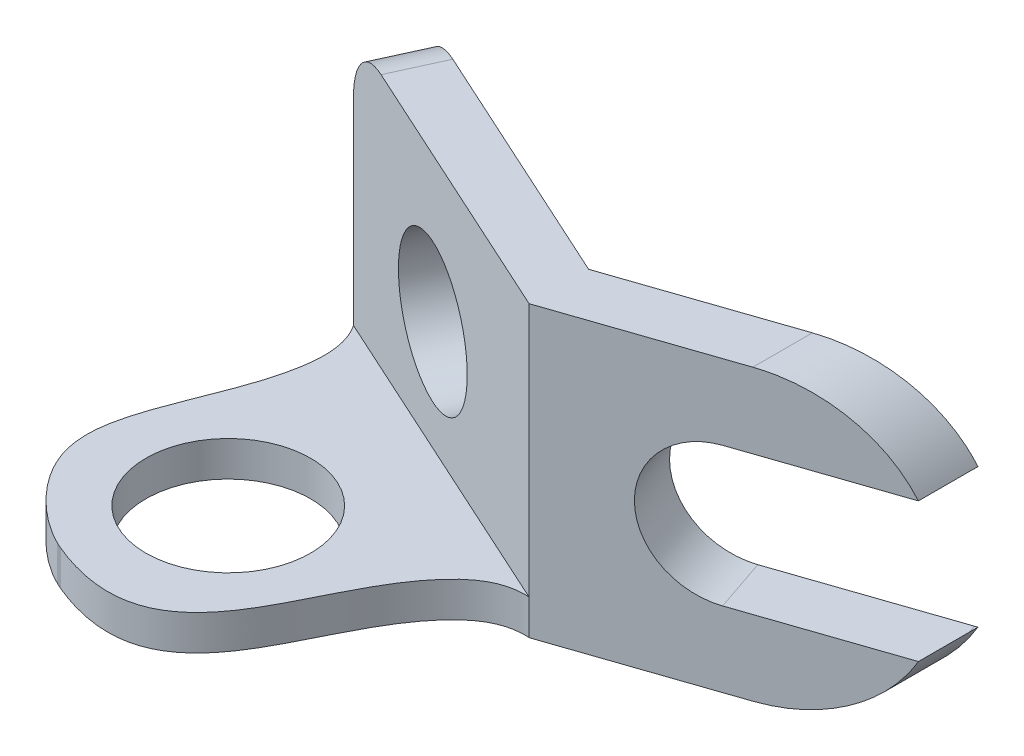
SolidWorks part; units mm, degrees
ref_plane "Front Plane" through (0, 0, 0) normal (0, 0, 1) x (1, 0, 0)
ref_plane "Top Plane" through (0, 0, 0) normal (0, 1, 0) x (1, 0, 0)
ref_plane "Right Plane" through (0, 0, 0) normal (1, 0, 0) x (0, 0, -1)
sketch "Sketch1" plane through (0, 0, 0) normal (0, 1, 0) x (1, 0, 0)
  line L0 (0, 0) -> (-54.0077, 24.6461)
  line L1 (-54.0077, 24.6461) -> (-58.049, 15.7903)
  line L2 (-58.049, 15.7903) -> (0, -10.7)
  line L3 (0, -10.7) -> (55, 8.0341)
  line L4 (0, 0) -> (55, 18.7341)
  line L5 (55, 18.7341) -> (55, 8.0341)
  dimension "D1" = 55
extrude "Boss-Extrude1" add sketch "Sketch1" against normal blind 52
fillet "Fillet1" radius 25 2 edges at (55, -52, -13.3841) (55, 0, -13.3841)
sketch "Sketch2" plane through (3.2657, 0, 9.5876) normal (0.3224, 0, 0.9466) x (0.9466, 0, -0.3224)
  line L0 (54.6531, -26) -> (23.9599, -26) construction
  line L1 (54.6531, -27) -> (54.6531, -25) construction
  line L2 (54.6531, -38.5) -> (23.9599, -38.5)
  line L3 (54.6531, -13.5) -> (23.9599, -13.5)
  line L4 (-3.45, 0) -> (28.2426, 0) construction
  line L5 (-3.45, -52) -> (28.2426, -52) construction
  arc A0 (54.6531, -38.5) -> (54.6531, -13.5) centre (54.6531, -26) ccw
  arc A1 (23.9599, -13.5) -> (23.9599, -38.5) centre (23.9599, -26) ccw
  point P4 (39.3065, -26)
  dimension "D1" = 25
  dimension "D2" = 26
  dimension "D3" = 26
extrude "Cut-Extrude1" cut sketch "Sketch2" against normal blind 52
fillet "Fillet2" radius 10 1 edges at (-56.0283, 0, -20.2182)
sketch "Sketch3" plane through (-4.0413, 0, 8.8558) normal (-0.4152, 0, 0.9097) x (0.9097, 0, 0.4152)
  line L0 (-59.3655, -52) -> (4.4422, -52) construction
  line L1 (4.4422, -52) -> (4.4422, 0) construction
  circle A0 centre (-30.5578, -26) radius 12.5
  point P6 (4.4422, -26)
  dimension "D1" = 25
  dimension "D2" = 26
  dimension "D3" = 35
extrude "Cut-Extrude2" cut sketch "Sketch3" against normal blind 52
sketch "Sketch5" plane through (-4.0413, 0, 8.8558) normal (-0.4152, 0, 0.9097) x (0.9097, 0, 0.4152)
  line L0 (-59.3655, -52) -> (-59.3655, -10) construction
  line L5 (-59.3655, -45.6812) -> (4.5899, -45.6812)
  line L6 (-59.3655, -45.6812) -> (-59.3655, -52)
  line L7 (-59.3655, -52) -> (4.5899, -52)
  line L8 (4.5899, -45.6812) -> (4.5899, -52)
  line L9 (-59.3655, -52) -> (4.4422, -52) construction
extrude "Boss-Extrude2" add sketch "Sketch5" along normal blind 52
sketch "Sketch6" plane through (0, -45.6812, 0) normal (0, 1, 0) x (1, 0, 0)
  line L0 (-21.4538, -58.0683) -> (-79.6372, -31.5167) construction
  line L1 (0, -10.7) -> (-58.049, 15.7903) construction
  circle A0 centre (-41.2751, -23.5073) radius 14.797
  spline S0 degree 3 poles (-58.049, 15.7903) (-55.8314, 12.4311) (-55.4685, -1.485) (-66.2119, -17.9808) (-64.125, -34.3343) (-55.0851, -42.9824) (-41.7189, -48.5121) (-33.0055, -48.3708) (-20.8559, -36.6853) (-16.0807, -18.8637) (-4.7278, -10.3811) (0, -10.7) knots 0 0 0 0 0.058811 0.209319 0.241844 0.351539 0.388555 0.574986 0.630926 0.892011 1 1 1 1
  point P2 (-41.2751, -23.5073)
  point P3 (-64.8837, -27.7088)
  line M4 (-58.049, 15.7903) -> (-79.6372, -31.5167)
  line M5 (-79.6372, -31.5167) -> (-21.4538, -58.0683)
  line M6 (-21.4538, -58.0683) -> (0.1344, -10.7613)
  line M13 (0.1344, -10.7613) -> (0, -10.7)
  dimension "D1" = 45
  dimension "D2" = 45
  dimension "D3" = 55
  dimension "D5" = 55
  dimension "D4" = 40
extrude "Cut-Extrude5" cut sketch "Sketch6" against normal blind 12 contours A0 | S0 M4 M5 | S0 M5 M6 M13
